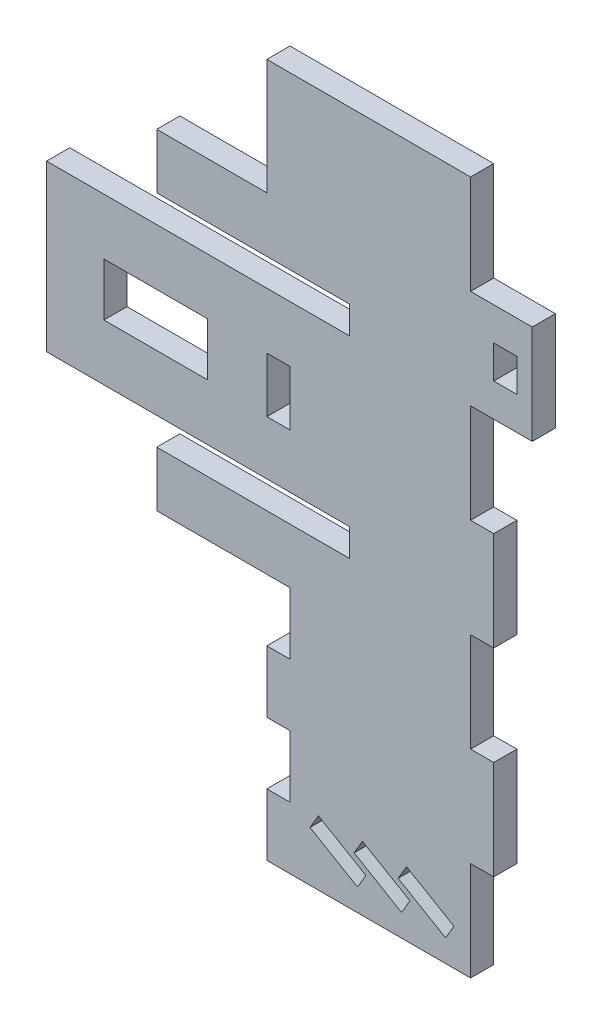
SolidWorks part; units mm, degrees
ref_plane "Front Plane" through (0, 0, 0) normal (0, 0, 1) x (1, 0, 0)
ref_plane "Top Plane" through (0, 0, 0) normal (0, 1, 0) x (1, 0, 0)
ref_plane "Right Plane" through (0, 0, 0) normal (1, 0, 0) x (0, 0, -1)
sketch "Sketch1" plane through (0, 0, 0) normal (0, 0, 1) x (1, 0, 0)
  line L1 (-67.3433, 67.6736) -> (-15.0193, 67.6736)
  line L2 (-67.3433, 67.6736) -> (-67.3433, -92.3464)
  line L3 (-67.3433, -92.3464) -> (-15.0193, -92.3464)
  line L4 (-15.0193, 67.6736) -> (-15.0193, -92.3464)
  dimension "D1" = 160.02
  dimension "D2" = 52.324
extrude "Boss-Extrude1" add sketch "Sketch1" along normal blind 5.334
sketch "Sketch2" plane through (0, 0, 5.334) normal (0, 0, 1) x (1, 0, 0)
  line L0 (-15.0193, -92.3464) -> (-15.0193, 67.6736) construction
  line L1 (-15.0193, 67.6736) -> (-20.3533, 67.6736)
  line L2 (-15.0193, 67.6736) -> (-15.0193, 44.8136)
  line L3 (-15.0193, 44.8136) -> (-20.3533, 44.8136)
  line L4 (-20.3533, 67.6736) -> (-20.3533, 44.8136)
  line L5 (-15.0193, 21.9536) -> (-20.3533, 21.9536)
  line L6 (-15.0193, 21.9536) -> (-15.0193, -0.9064)
  line L7 (-15.0193, -0.9064) -> (-20.3533, -0.9064)
  line L8 (-20.3533, 21.9536) -> (-20.3533, -0.9064)
  line L9 (-20.3533, -69.4864) -> (-20.3533, -46.6264) construction
  line L10 (-15.0193, -23.7664) -> (-20.3533, -23.7664)
  line L11 (-15.0193, -23.7664) -> (-15.0193, -46.6264)
  line L12 (-15.0193, -46.6264) -> (-20.3533, -46.6264)
  line L13 (-20.3533, -23.7664) -> (-20.3533, -46.6264)
  line L14 (-15.0193, -92.3464) -> (-20.3533, -92.3464)
  line L15 (-15.0193, -92.3464) -> (-15.0193, -69.4864)
  line L16 (-15.0193, -69.4864) -> (-20.3533, -69.4864)
  line L17 (-20.3533, -92.3464) -> (-20.3533, -69.4864)
  line L18 (-20.3533, -23.7664) -> (-20.3533, -0.9064) construction
  line L19 (-20.3533, 21.9536) -> (-20.3533, 44.8136) construction
  dimension "D1" = 5.334
extrude "Cut-Extrude1" cut sketch "Sketch2" against normal through all
sketch "Sketch3" plane through (-67.3433, 0, 0) normal (-1, 0, 0) x (0, 0, 1)
  line L0 (0, 67.6736) -> (0, -92.3464) construction
  line L1 (0, 21.9536) -> (5.334, 21.9536)
  line L2 (0, 21.9536) -> (0, -16.1464)
  line L3 (0, -16.1464) -> (5.334, -16.1464)
  line L4 (5.334, 21.9536) -> (5.334, -16.1464)
  line L5 (5.334, 67.6736) -> (5.334, -92.3464) construction
  line L6 (5.334, -92.3464) -> (0, -92.3464) construction
  dimension "D1" = 38.1
  dimension "D2" = 76.2
extrude "Boss-Extrude2" add sketch "Sketch3" along normal blind 50.8
sketch "Sketch4" plane through (0, 0, 5.334) normal (0, 0, 1) x (1, 0, 0)
  line L0 (-67.3433, 21.9536) -> (-67.3433, -16.1464) construction
  line L1 (-104.9353, 8.9996) -> (-81.0593, 8.9996)
  line L2 (-104.9353, 8.9996) -> (-104.9353, -3.1924)
  line L3 (-104.9353, -3.1924) -> (-81.0593, -3.1924)
  line L4 (-81.0593, 8.9996) -> (-81.0593, -3.1924)
  line L5 (-67.3433, 2.9036) -> (-118.1433, 2.9036) construction
  line L6 (-118.1433, -16.1464) -> (-118.1433, 21.9536) construction
  dimension "D1" = 12.192
  dimension "D2" = 6.096
  dimension "D3" = 23.876
  dimension "D4" = 37.084
extrude "Cut-Extrude2" cut sketch "Sketch4" against normal through all
sketch "Sketch5" plane through (0, 0, 5.334) normal (0, 0, 1) x (1, 0, 0)
  line L0 (-118.1433, 2.9036) -> (-30.6389, 2.9036) construction
  line L1 (-67.3433, 21.9536) -> (-48.2933, 21.9536)
  line L2 (-67.3433, 21.9536) -> (-67.3433, 28.3036)
  line L3 (-67.3433, 28.3036) -> (-48.2933, 28.3036)
  line L4 (-48.2933, 21.9536) -> (-48.2933, 28.3036)
  line L5 (-118.1433, -16.1464) -> (-118.1433, 21.9536) construction
  line L6 (-48.2933, -16.1464) -> (-48.2933, -22.4964)
  line L7 (-67.3433, -22.4964) -> (-48.2933, -22.4964)
  line L8 (-67.3433, -16.1464) -> (-67.3433, -22.4964)
  line L9 (-67.3433, -16.1464) -> (-48.2933, -16.1464)
  dimension "D1" = 19.05
  dimension "D2" = 6.35
extrude "Cut-Extrude3" cut sketch "Sketch5" against normal through all
sketch "Sketch6" plane through (-67.3433, 0, 0) normal (-1, 0, 0) x (0, 0, 1)
  line L0 (0, 67.6736) -> (0, 28.3036) construction
  line L1 (5.334, 28.3036) -> (0, 28.3036)
  line L2 (5.334, 28.3036) -> (5.334, 41.0036)
  line L3 (5.334, 41.0036) -> (0, 41.0036)
  line L4 (0, 28.3036) -> (0, 41.0036)
  dimension "D1" = 12.7
extrude "Boss-Extrude3" add sketch "Sketch6" along normal blind 25.4
sketch "Sketch7" plane through (-67.3433, 0, 0) normal (-1, 0, 0) x (0, 0, 1)
  line L0 (5.334, -22.4964) -> (5.334, -92.3464) construction
  line L1 (0, -22.4964) -> (5.334, -22.4964)
  line L2 (0, -22.4964) -> (0, -35.1964)
  line L3 (0, -35.1964) -> (5.334, -35.1964)
  line L4 (5.334, -22.4964) -> (5.334, -35.1964)
  dimension "D1" = 12.7
extrude "Boss-Extrude4" add sketch "Sketch7" along normal blind 25.4
sketch "Sketch8" plane through (0, 0, 5.334) normal (0, 0, 1) x (1, 0, 0)
  line L0 (-67.3433, -35.1964) -> (-67.3433, -92.3464) construction
  line L1 (-67.3433, -35.1964) -> (-62.0093, -35.1964)
  line L2 (-67.3433, -35.1964) -> (-67.3433, -49.4839)
  line L3 (-67.3433, -49.4839) -> (-62.0093, -49.4839)
  line L4 (-62.0093, -35.1964) -> (-62.0093, -49.4839)
  line L5 (-67.3433, -63.7714) -> (-62.0093, -63.7714)
  line L6 (-67.3433, -63.7714) -> (-67.3433, -78.0589)
  line L7 (-67.3433, -78.0589) -> (-62.0093, -78.0589)
  line L8 (-62.0093, -63.7714) -> (-62.0093, -78.0589)
  line L9 (-62.0093, -78.0589) -> (-62.0093, -92.3464) construction
  line L10 (-67.3433, -92.3464) -> (-20.3533, -92.3464) construction
  line L11 (-62.0093, -49.4839) -> (-62.0093, -63.7714) construction
  dimension "D1" = 5.334
extrude "Cut-Extrude4" cut sketch "Sketch8" against normal through all
sketch "Sketch9" plane through (0, 0, 5.334) normal (0, 0, 1) x (1, 0, 0)
  line L0 (-62.0093, -49.4839) -> (-62.0093, -35.1964) construction
  line L1 (-67.3433, 8.9996) -> (-62.0093, 8.9996)
  line L2 (-67.3433, 8.9996) -> (-67.3433, -3.7004)
  line L3 (-67.3433, -3.7004) -> (-62.0093, -3.7004)
  line L4 (-62.0093, 8.9996) -> (-62.0093, -3.7004)
  line L5 (-81.0593, 8.9996) -> (-104.9353, 8.9996) construction
  dimension "D1" = 5.334
  dimension "D2" = 0
  dimension "D3" = 12.7
  dimension "D4" = 0
extrude "Cut-Extrude5" cut sketch "Sketch9" against normal through all
sketch "Sketch10" plane through (0, 0, 5.334) normal (0, 0, 1) x (1, 0, 0)
  line L0 (-37.716, -92.3464) -> (-62.0093, -78.0589) construction
  line L1 (-67.3433, -92.3464) -> (-20.3533, -92.3464) construction
  line L2 (-57.3794, -80.7819) -> (-46.4323, -87.2201)
  line L3 (-57.3794, -80.7819) -> (-55.448, -77.4977)
  line L4 (-46.4323, -87.2201) -> (-44.5009, -83.936)
  line L5 (-55.448, -77.4977) -> (-44.5009, -83.936)
  line L7 (-45.288, -77.4977) -> (-34.3409, -83.936)
  line L8 (-47.2194, -80.7819) -> (-45.288, -77.4977)
  line L9 (-47.2194, -80.7819) -> (-36.2723, -87.2201)
  line L10 (-36.2723, -87.2201) -> (-34.3409, -83.936)
  line L11 (-35.128, -77.4977) -> (-24.1809, -83.936)
  line L12 (-37.0594, -80.7819) -> (-35.128, -77.4977)
  line L13 (-37.0594, -80.7819) -> (-26.1123, -87.2201)
  line L14 (-26.1123, -87.2201) -> (-24.1809, -83.936)
  dimension "D1" = 3.81
  dimension "D2" = 12.7
  dimension "D3" = 3
extrude "Cut-Extrude6" cut sketch "Sketch10" against normal through all
sketch "Sketch11" plane through (-15.0193, 0, 0) normal (1, 0, 0) x (0, 0, -1)
  line L1 (-5.334, 44.8136) -> (0, 44.8136)
  line L2 (-5.334, 44.8136) -> (-5.334, 21.9536)
  line L3 (-5.334, 21.9536) -> (0, 21.9536)
  line L4 (0, 44.8136) -> (0, 21.9536)
extrude "Boss-Extrude5" add sketch "Sketch11" along normal blind 8.89
sketch "Sketch12" plane through (0, 0, 5.334) normal (0, 0, 1) x (1, 0, 0)
  line L0 (-6.1293, 33.3836) -> (-23.8877, 33.3836) construction
  line L1 (-15.0193, 37.1936) -> (-9.6853, 37.1936)
  line L2 (-15.0193, 37.1936) -> (-15.0193, 29.5736)
  line L3 (-15.0193, 29.5736) -> (-9.6853, 29.5736)
  line L4 (-9.6853, 37.1936) -> (-9.6853, 29.5736)
  line L5 (-6.1293, 44.8136) -> (-6.1293, 21.9536) construction
  line L6 (-20.3533, 67.6736) -> (-20.3533, 44.8136) construction
  dimension "D1" = 5.334
  dimension "D2" = 7.62
  dimension "D3" = 3.81
  dimension "D4" = 5.334
extrude "Cut-Extrude7" cut sketch "Sketch12" against normal through all
equation "\"MDF\"= .21in"
equation "\"Foamcore\"= .13in"
equation "\"Gmaterial\"= \"MDF\""
equation "\"D2@Sketch1\"=2*\"MDF\"+1.64"
equation "\"D1@Boss-Extrude1\"=\"MDF\""
equation "\"D1@Sketch2\"=\"MDF\""
equation "\"D1@Sketch8\"=\"MDF\""
equation "\"D1@Sketch9\"=\"MDF\""
equation "\"D1@Sketch12\"=\"MDF\""
equation "\"D4@Sketch12\"=\"MDF\""
